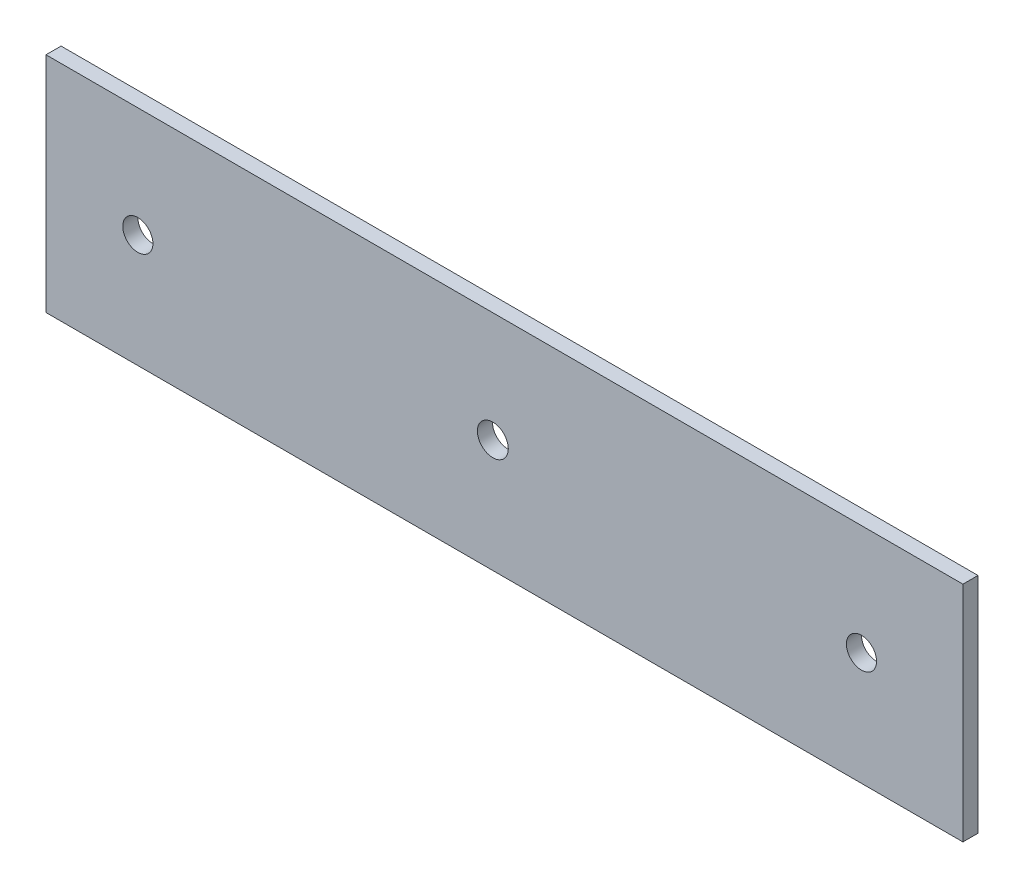
SolidWorks part; units mm, degrees
ref_plane "Front Plane" through (0, 0, 0) normal (0, 0, 1) x (1, 0, 0)
ref_plane "Top Plane" through (0, 0, 0) normal (0, 1, 0) x (1, 0, 0)
ref_plane "Right Plane" through (0, 0, 0) normal (1, 0, 0) x (0, 0, -1)
sketch "Sketch1" plane through (0, 0, 0) normal (0, 0, 1) x (1, 0, 0)
  line L1 (56.8583, 23.1921) -> (249.962, 23.1921)
  line L2 (56.8583, 23.1921) -> (56.8583, -23.8263)
  line L3 (56.8583, -23.8263) -> (249.962, -23.8263)
  line L4 (249.962, 23.1921) -> (249.962, -23.8263)
  circle A0 centre (76.2, 0) radius 3.175
  circle A1 centre (228.6, 0) radius 3.175
  circle A2 centre (150.964, 0) radius 3.2512
  circle A3 centre (150.964, 0) radius 3.175 construction
  dimension "D1" = 6.5024
extrude "Boss-Extrude1" add sketch "Sketch1" along normal blind 3.175
